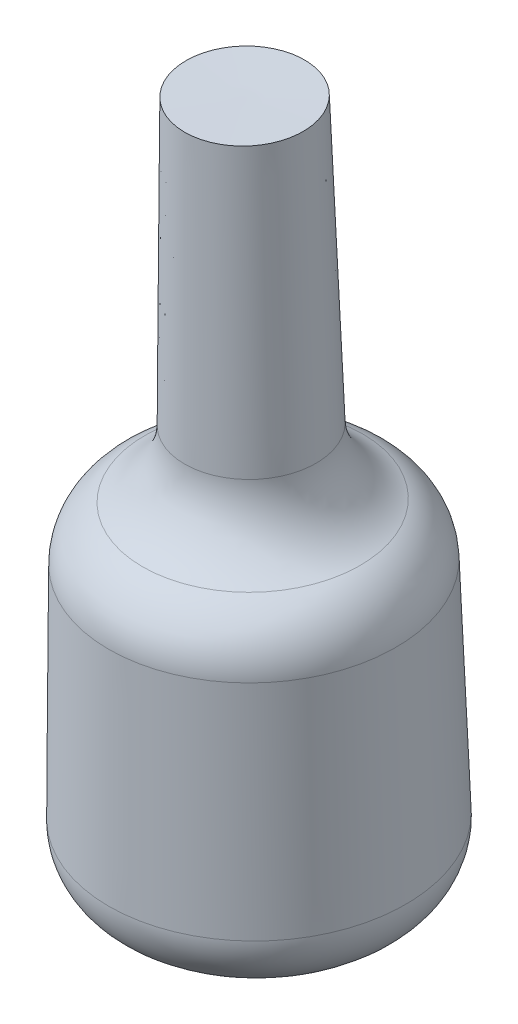
SolidWorks part; units mm, degrees
ref_plane "Front Plane" through (0, 0, 0) normal (0, 0, 1) x (1, 0, 0)
ref_plane "Top Plane" through (0, 0, 0) normal (0, 1, 0) x (1, 0, 0)
ref_plane "Right Plane" through (0, 0, 0) normal (1, 0, 0) x (0, 0, -1)
sketch "Sketch1" plane through (0, 0, 0) normal (1, 0, 0) x (0, 0, -1)
  line L0 (-18.3947, 55.3136) -> (-15.8039, -58.4226)
  line L1 (-15.8039, -58.4226) -> (-40.6756, -58.4226)
  line L2 (-40.6756, -58.4226) -> (-40.6756, -4.2748)
  line L3 (-18.3947, 55.3136) -> (-28.2319, 55.3136)
  line L4 (-28.2319, 55.3136) -> (-28.2319, 8.1688)
  arc A1 (-40.6756, -4.2748) -> (-28.2319, 8.1688) centre (-40.6756, 8.1688) ccw
  point P7 (-40.6756, -4.2748)
revolve "Revolve1" add sketch "Sketch1" angle 360 about L0
fillet "Fillet1" radius 10 1 edges at (0, -58.4226, 40.6756)
fillet "Fillet3" radius 10 1 edges at (0, -4.2748, 40.6756)
